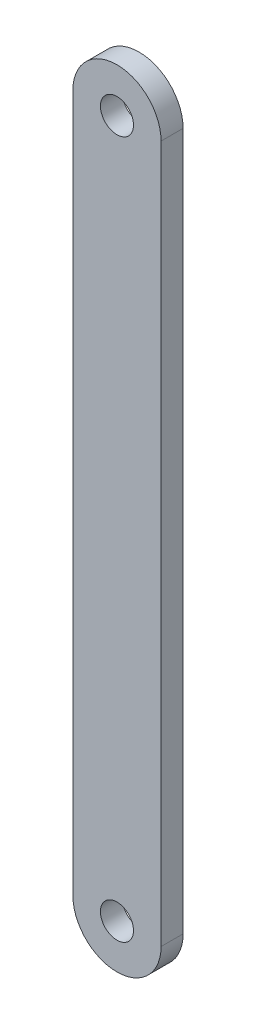
SolidWorks part; units mm, degrees
ref_plane "Front Plane" through (0, 0, 0) normal (0, 0, 1) x (1, 0, 0)
ref_plane "Top Plane" through (0, 0, 0) normal (0, 1, 0) x (1, 0, 0)
ref_plane "Right Plane" through (0, 0, 0) normal (1, 0, 0) x (0, 0, -1)
sketch "Sketch1" plane through (0, 0, 0) normal (0, 0, 1) x (1, 0, 0)
  line L0 (0, 0) -> (0, 32.1564)
  line L1 (4.064, 32.1564) -> (4.064, 0)
  arc A0 (0, 32.1564) -> (4.064, 32.1564) centre (2.032, 32.1564) cw
  arc A1 (4.064, 0) -> (0, 0) centre (2.032, 0) cw
  circle A2 centre (2.032, 32.1564) radius 0.762
  circle A3 centre (2.032, 0) radius 0.762
  dimension "D2" = 2.032
  dimension "D3" = 1.524
  dimension "D4" = 1.524
  dimension "D1" = 32.1564
extrude "Boss-Extrude1" add sketch "Sketch1" along normal blind 1.016
